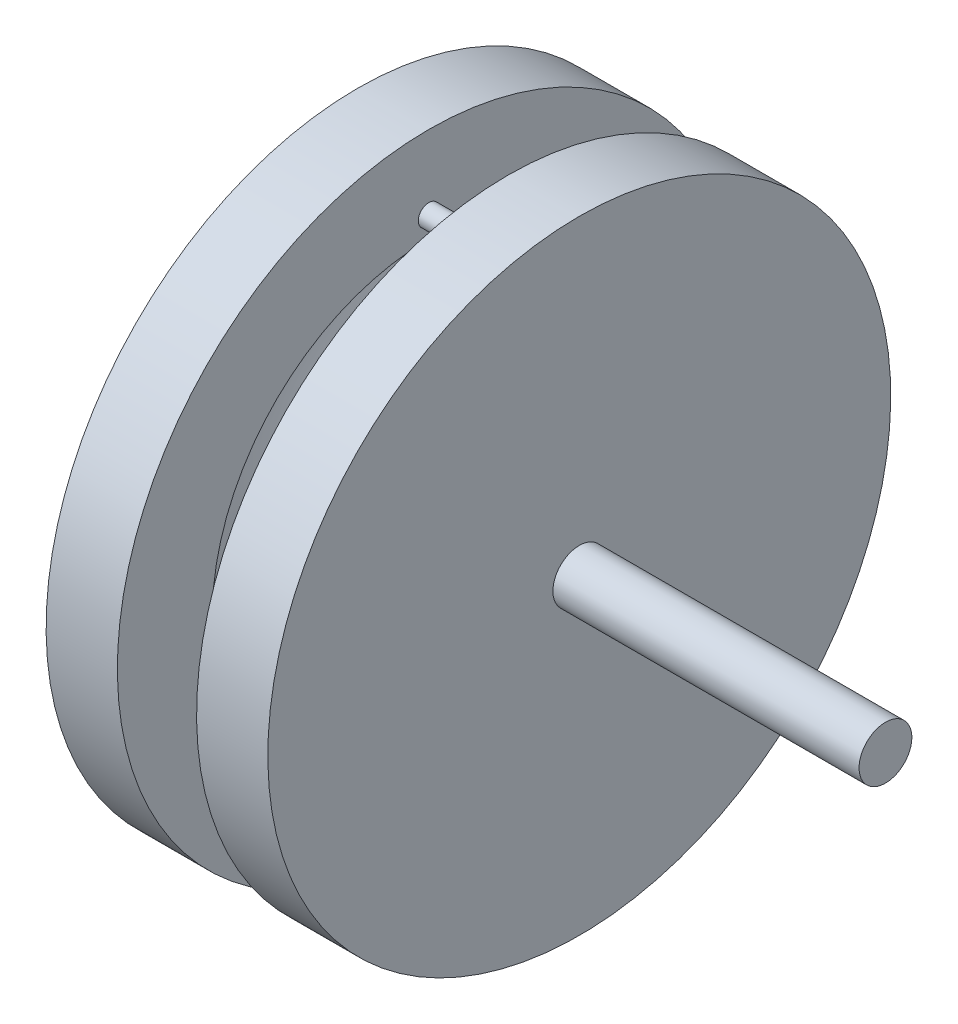
SolidWorks part; units mm, degrees
ref_plane "前视基准面" through (0, 0, 0) normal (0, 0, 1) x (1, 0, 0)
ref_plane "上视基准面" through (0, 0, 0) normal (0, 1, 0) x (1, 0, 0)
ref_plane "右视基准面" through (0, 0, 0) normal (1, 0, 0) x (0, 0, -1)
other "Configuration Table"
sketch "草图1" plane through (0, 0, 0) normal (0, 0, 1) x (1, 0, 0)
  line L0 (0, 0) -> (-21, 0)
  line L1 (-21, 0) -> (-21, 29.5)
  line L2 (-21, 29.5) -> (-14.25, 29.5)
  line L3 (0, 29.5) -> (0, 0)
  line L4 (-21, 29.5) -> (-14.25, 29.5)
  line L5 (0, 29.5) -> (-6.75, 29.5)
  line L7 (0, 0) -> (0, 2.5)
  line L8 (0, 2.5) -> (29, 2.5)
  line L9 (29, 2.5) -> (29, 0)
  line L10 (29, 0) -> (0, 0)
  line L11 (-14.25, 29.5) -> (-14.25, 20.5)
  line L12 (-6.75, 29.5) -> (-6.75, 21)
  line L14 (-6.75, 29.5) -> (0, 29.5)
  spline S0 degree 2 poles (-14.25, 20.5) (-10.2711, 9.2546) (-6.75, 21) knots 0 0 0 1 1 1
  point P14 (29, 1.25)
  dimension "D5" = 29.5
  dimension "D1" = 21
  dimension "D2" = 6.75
  dimension "D3" = 6.75
  dimension "D4" = 14.5
  dimension "D6" = 10.5
  dimension "D7" = 2.5
  dimension "D8" = 29
revolve "旋转1" add sketch "草图1" angle 360 about L0
sketch "草图2" plane through (0, 0, 0) normal (1, 0, 0) x (0, 0, -1)
  line L0 (0, 29.5) -> (0, 22.5)
  line L1 (0, 0) -> (6.7819, 0)
  circle A0 centre (0, 0) radius 29.5 construction
  circle A1 centre (0, 22.5) radius 1
  circle A2 centre (0, -22.5) radius 1
extrude "凸台-拉伸1" add sketch "草图2" against normal blind 20 contours A1 | A2
